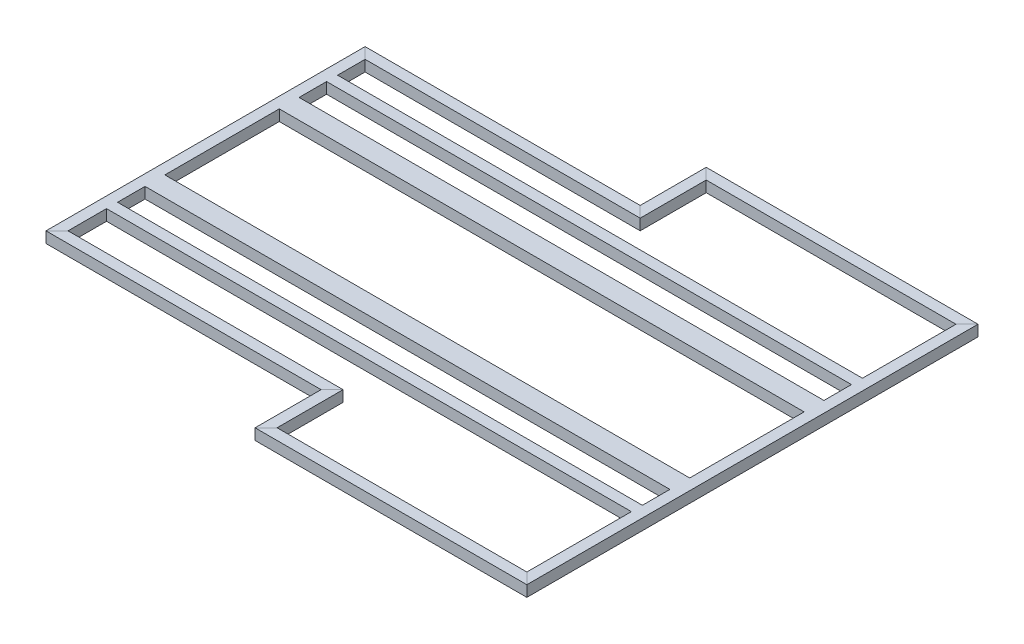
SolidWorks part; units mm, degrees
ref_plane "Front Plane" through (0, 0, 0) normal (0, 0, 1) x (1, 0, 0)
ref_plane "Top Plane" through (0, 0, 0) normal (0, 1, 0) x (1, 0, 0)
ref_plane "Right Plane" through (0, 0, 0) normal (1, 0, 0) x (0, 0, -1)
sketch "Sketch1" plane through (0, 0, 0) normal (0, 1, 0) x (1, 0, 0)
  line L0 (1250, -1400) -> (1250, -1700)
  line L1 (0, 0) -> (1250, 0)
  line L2 (0, 0) -> (0, -1400)
  line L3 (0, -1400) -> (1250, -1400)
  line L5 (1250, 300) -> (2435, 300)
  line L6 (1250, 300) -> (1250, 0)
  line L7 (1250, -1700) -> (2435, -1700)
  line L8 (2435, 300) -> (2435, -1700)
  dimension "D1" = 2000
  dimension "D2" = 300
  dimension "D3" = 300
  dimension "D4" = 2435
  dimension "D5" = 1250
sketch "Sketch2" plane through (0, 0, 0) normal (1, 0, 0) x (0, 0, -1)
  line L1 (-25, -25) -> (25, -25)
  line L2 (-25, -25) -> (-25, 25)
  line L3 (-25, 25) -> (25, 25)
  line L4 (25, -25) -> (25, 25)
  line L5 (-25, -25) -> (25, 25) construction
  line L6 (-25, 25) -> (25, -25) construction
  point P0 (0, 0)
  dimension "D1" = 50
  dimension "D2" = 50
sweep "Sweep1" add profiles "Sketch2" path "Sketch1"
ref_plane "Plane1" through (0, 0, 675) normal (0, 0, -1) x (-1, 0, 0)
sketch "Sketch3" plane through (-25, 0, 0) normal (-1, 0, 0) x (0, 0, 1)
  line L0 (1425, 25) -> (-25, 25) construction
  line L1 (325, 25) -> (415, 25)
  line L2 (325, 25) -> (325, -25)
  line L3 (325, -25) -> (355, -25)
  line L4 (415, 25) -> (415, -25)
  line L5 (1425, -25) -> (-25, -25) construction
  line L6 (-25, 25) -> (-25, -25) construction
  line L7 (330, 20) -> (410, 20)
  line L8 (330, 20) -> (330, -20)
  line L9 (330, -20) -> (355, -20)
  line L10 (410, 20) -> (410, -20)
  line L11 (355, -20) -> (355, -25)
  line L12 (355, -20) -> (355, -25)
  line L13 (385, -20) -> (385, -25)
  line L14 (385, -25) -> (415, -25)
  line L15 (385, -20) -> (410, -20)
  line L16 (325, -25) -> (355, -25)
  line L17 (325, -25) -> (355, -25)
  point P18 (370, 20)
  line M9 (1425, 25) -> (-25, 25)
  line M11 (-25, -25) -> (1425, -25)
  dimension "D1" = 90
  dimension "D2" = 5
  dimension "D3" = 5
  dimension "D4" = 5
  dimension "D5" = 5
  dimension "D6" = 350
  dimension "D7" = 30
  dimension "D8" = 15
extrude "Boss-Extrude1" add sketch "Sketch3" against normal up to surface (2435 mm away) contours L15 L13 L4 L2 L11 L9 L8 L7 L10 M11 M9 up to face at (2410, 0, 700)
sketch "Sketch5" plane through (25, 0, 0) normal (1, 0, 0) x (0, 0, -1)
  line L16 (-385, -25) -> (-355, -25)
  line L17 (-355, -25) -> (-355, -20)
  line L18 (-355, -20) -> (-330, -20)
  line L19 (-330, -20) -> (-330, 20)
  line L20 (-330, 20) -> (-410, 20)
  line L21 (-410, 20) -> (-410, -20)
  line L22 (-410, -20) -> (-385, -20)
  line L23 (-385, -20) -> (-385, -25)
  line L24 (-385, -25) -> (-355, -25)
  line L25 (-355, -25) -> (-355, -20)
  line L26 (-355, -20) -> (-330, -20)
  line L27 (-330, -20) -> (-330, 20)
  line L28 (-330, 20) -> (-410, 20)
  line L29 (-410, 20) -> (-410, -20)
  line L30 (-410, -20) -> (-385, -20)
  line L31 (-385, -20) -> (-385, -25)
  dimension "D1" = 0
extrude "Cut-Extrude1" cut sketch "Sketch5" against normal blind 80
mirror "Mirror1" about plane through (0, 0, 675) normal (0, 0, -1) of "Cut-Extrude1", "Boss-Extrude1"
sketch "Sketch6" plane through (-25, 0, 0) normal (-1, 0, 0) x (0, 0, 1)
  line L0 (1425, 25) -> (-25, 25) construction
  line L1 (150, 25) -> (200, 25)
  line L2 (150, 25) -> (150, -25)
  line L3 (150, -25) -> (200, -25)
  line L4 (200, 25) -> (200, -25)
  line L5 (355, -25) -> (-25, -25) construction
  line L6 (-25, 25) -> (-25, -25) construction
  line L7 (155, 20) -> (195, 20)
  line L8 (155, 20) -> (155, -20)
  line L9 (155, -20) -> (195, -20)
  line L10 (195, 20) -> (195, -20)
  point P12 (175, 25)
  dimension "D1" = 50
  dimension "D2" = 5
  dimension "D3" = 5
  dimension "D4" = 5
  dimension "D5" = 5
  dimension "D6" = 175
extrude "Boss-Extrude2" add sketch "Sketch6" against normal up to surface (2435 mm away) up to face at (2410, 0, 25)
sketch "Sketch7" plane through (-25, 0, 0) normal (-1, 0, 0) x (0, 0, 1)
  line L4 (195, 20) -> (155, 20)
  line L5 (195, -20) -> (195, 20)
  line L6 (155, -20) -> (195, -20)
  line L7 (155, 20) -> (155, -20)
  line L8 (195, 20) -> (155, 20)
  line L9 (195, -20) -> (195, 20)
  line L10 (155, -20) -> (195, -20)
  line L11 (155, 20) -> (155, -20)
  dimension "D1" = 0
extrude "Cut-Extrude2" cut sketch "Sketch7" against normal blind 80
mirror "Mirror2" about plane through (0, 0, 675) normal (0, 0, -1) of "Cut-Extrude2", "Boss-Extrude2"
equation "\"D3@Sketch1\"=\"D2@Sketch1\""
equation "\"D2@Sketch2\"=\"D1@Sketch2\""
equation "\"D3@Sketch3\"=\"D2@Sketch3\""
equation "\"D4@Sketch3\"=\"D2@Sketch3\""
equation "\"D5@Sketch3\"=\"D2@Sketch3\""
